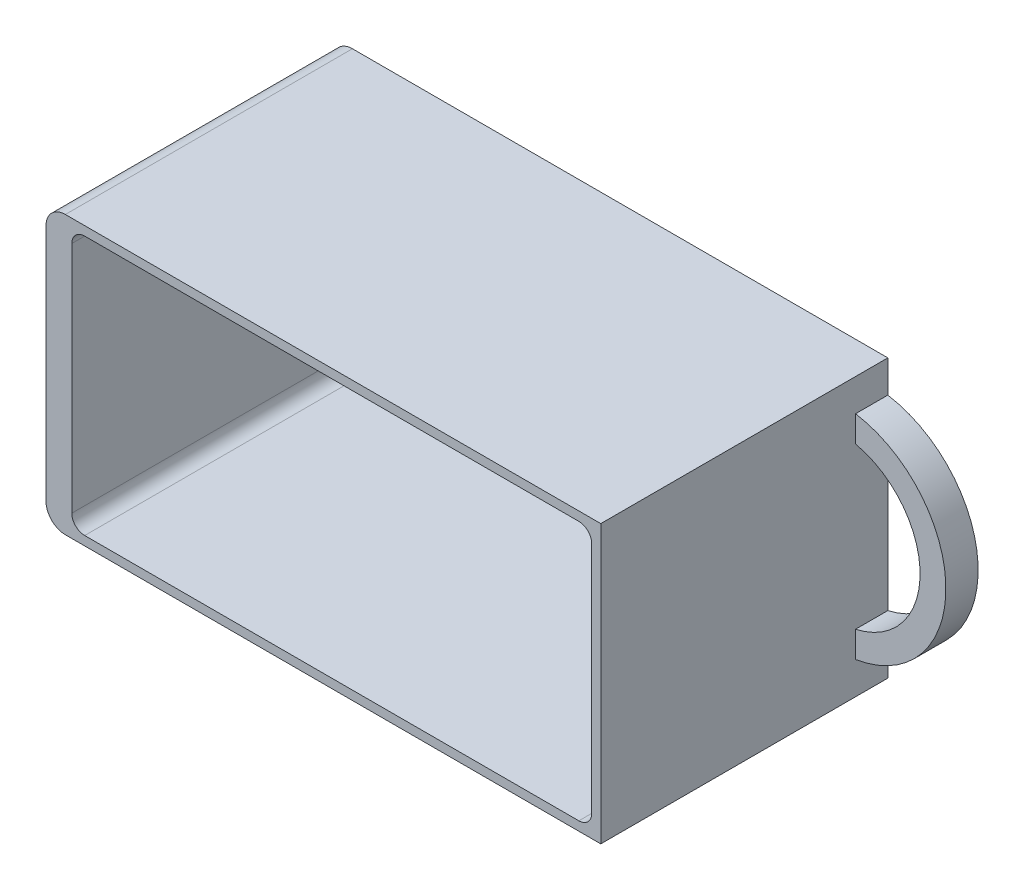
SolidWorks part; units mm, degrees
ref_plane "Спереди" through (0, 0, 0) normal (0, 0, 1) x (1, 0, 0)
ref_plane "Сверху" through (0, 0, 0) normal (0, 1, 0) x (1, 0, 0)
ref_plane "Справа" through (0, 0, 0) normal (1, 0, 0) x (0, 0, -1)
ref_plane "Плоскость4" through (0, 0, 22.25) normal (0, 0, 1) x (1, 0, 0)
sketch "Эскиз1" plane through (0, 0, 22.25) normal (0, 0, 1) x (1, 0, 0)
  line L0 (90, -21.5) -> (90, 21.5)
  line L1 (90, 21.5) -> (4, 21.5)
  line L2 (4, 21.5) -> (4, -21.5)
  line L3 (4, -21.5) -> (90, -21.5)
extrude "Бобышка-Вытянуть1" add sketch "Эскиз1" against normal blind 39.5
sketch "Эскиз2" plane through (0, 0, -17.25) normal (0, 0, -1) x (-1, 0, 0)
  line L0 (-90, -21.5) -> (-90, -16.5)
  line L1 (-90, 16.5) -> (-90, 21.5)
  line L2 (-90, 21.5) -> (-4, 21.5)
  line L3 (-4, 21.5) -> (-4, -21.5)
  line L4 (-4, -21.5) -> (-90, -21.5)
  line L5 (-90, -12.4284) -> (-90, 12.4284)
  arc A0 (-90, -16.5) -> (-90, 16.5) centre (-87.2768, 0) cw
  arc A1 (-90, 12.4284) -> (-90, -12.4284) centre (-87.2768, 0) ccw
extrude "Бобышка-Вытянуть2" add sketch "Эскиз2" along normal blind 5
sketch "Эскиз3" plane through (0, 0, 22.25) normal (0, 0, 1) x (1, 0, 0)
  line L0 (88.6, -20.1) -> (88.6, 20.1)
  line L1 (88.6, 20.1) -> (8, 20.1)
  line L2 (8, 20.1) -> (8, -20.1)
  line L3 (8, -20.1) -> (88.6, -20.1)
extrude "Вырез-Вытянуть1" cut sketch "Эскиз3" against normal blind 43.6
hole_wizard "Диаметр отверстия Ø8.3 (8.3)1" positions "Эскиз5" profile "Эскиз4" hole size "Ø8.3" standard "Ansi Metric"
sketch "Эскиз5" plane through (4, 0, 0) normal (-1, 0, 0) x (0, 0, 1)
  point P0 (0, 0)
sketch "Эскиз4" plane through (4, 0, 0) normal (0, 1, 0) x (0, 0, 1)
  line L0 (0, 0) -> (0, 3.2)
  line L1 (0, 3.2) -> (4.15, 3.2)
  line L2 (4.15, 3.2) -> (4.15, 0)
  line L5 (4.15, 0) -> (0, 0)
  line L10 (0, 3.2) -> (-4.15, 3.2) construction
  line L11 (0, -6.35) -> (0, 107.95) construction
  dimension "Диаметр отверстия" = 8.3
  dimension "Глубина отверстия" = 3.2
  dimension "Угол заточки сверла" = 180
fillet "Скругление1" radius 3 2 edges at (4, -21.5, 0) (4, 21.5, 0)
sketch "Эскиз6" plane through (4, 0, 0) normal (-1, 0, 0) x (0, 0, 1)
  circle A0 centre (0, 0) radius 4.15 construction
  circle A1 centre (0, 0) radius 4.15
extrude "Бобышка-Вытянуть3" add sketch "Эскиз6" against normal blind 4
fillet "Скругление2" radius 2 8 edges at (88.6, -20.1, 0.45) (88.6, 20.1, 0.45) (88.6, 0, -21.35) (48.3, -20.1, -21.35) (8, -20.1, 0.45) (8, 20.1, 0.45) (48.3, 20.1, -21.35) (8, 0, -21.35)
